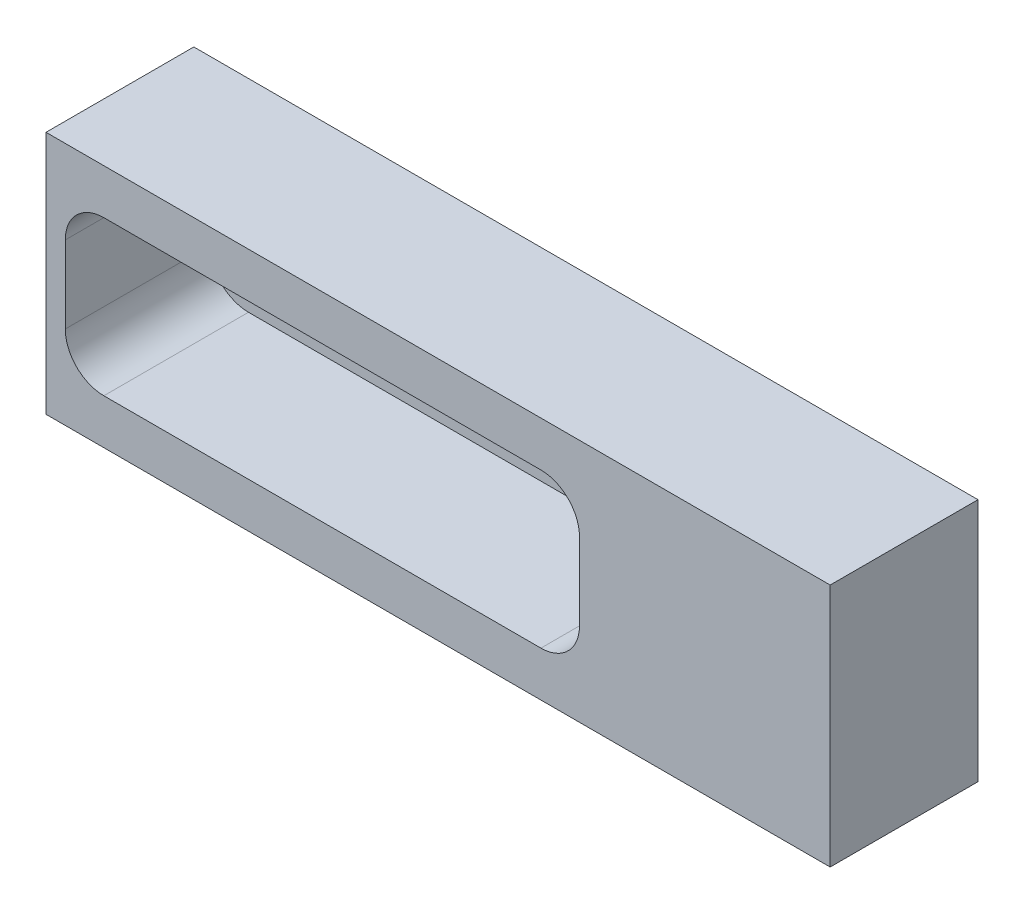
SolidWorks part; units mm, degrees
ref_plane "Front Plane" through (0, 0, 0) normal (0, 0, 1) x (1, 0, 0)
ref_plane "Top Plane" through (0, 0, 0) normal (0, 1, 0) x (1, 0, 0)
ref_plane "Right Plane" through (0, 0, 0) normal (1, 0, 0) x (0, 0, -1)
sketch "Sketch1" plane through (0, 0, 0) normal (1, 0, 0) x (0, 0, -1)
  line L1 (-12.5, -19) -> (12.5, -19)
  line L2 (-12.5, -19) -> (-12.5, 19)
  line L3 (-12.5, 19) -> (12.5, 19)
  line L4 (12.5, -19) -> (12.5, 19)
  line L5 (-12.5, -19) -> (12.5, 19) construction
  line L6 (-12.5, 19) -> (12.5, -19) construction
  point P0 (0, 0)
  dimension "D1" = 25
  dimension "D2" = 38
extrude "Boss-Extrude1" add sketch "Sketch1" along normal blind 122
sketch "Sketch2" plane through (0, 0, 12.5) normal (0, 0, 1) x (1, 0, 0)
  line L0 (0, 19) -> (0, -19) construction
  line L1 (3, -12) -> (83, -12)
  line L2 (3, -12) -> (3, 12)
  line L3 (3, 12) -> (83, 12)
  line L4 (83, -12) -> (83, 12)
  line L5 (3, -12) -> (83, 12) construction
  line L6 (3, 12) -> (83, -12) construction
  line L7 (122, 19) -> (0, 19) construction
  point P0 (43, 0)
  dimension "D1" = 80
  dimension "D2" = 24
  dimension "D3" = 3
  dimension "D4" = 7
extrude "Cut-Extrude1" cut sketch "Sketch2" against normal blind 22.5
fillet "Fillet1" radius 6 1 edges at (3, 12, 1.25)
fillet "Fillet2" radius 6 1 edges at (3, -12, 1.25)
fillet "Fillet3" radius 6 1 edges at (83, -12, 1.25)
fillet "Fillet4" radius 6 1 edges at (83, 12, 1.25)
sketch "Sketch3" plane through (0, 0, -10) normal (0, 0, 1) x (1, 0, 0)
  line L0 (0, 19) -> (0, -19) construction
  circle A0 centre (43, 0) radius 9.2
  dimension "D1" = 18.4
  dimension "D2" = 43
extrude "Cut-Extrude2" cut sketch "Sketch3" against normal through all
chamfer "Chamfer2" distance 2 angle 45 4 edges at (61, 19, -12.5) (122, 0, -12.5) (61, -19, -12.5) (0, 0, -12.5)
